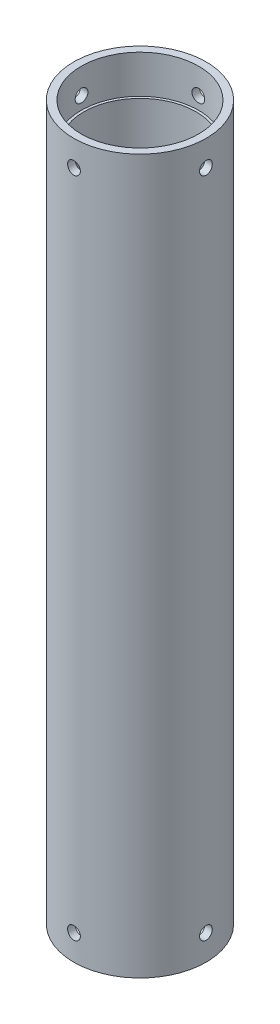
SolidWorks part; units mm, degrees
material "6061-T6 (SS)"
ref_plane "정면" through (0, 0, 0) normal (0, 0, 1) x (1, 0, 0)
ref_plane "윗면" through (0, 0, 0) normal (0, 1, 0) x (1, 0, 0)
ref_plane "우측면" through (0, 0, 0) normal (1, 0, 0) x (0, 0, -1)
sketch "스케치1" plane through (0, 0, 0) normal (0, 1, 0) x (1, 0, 0)
  circle A0 centre (0, 0) radius 26
  circle A1 centre (0, 0) radius 22.05
  dimension "D1" = 52
  dimension "D2" = 44.1
extrude "보스-돌출1" add sketch "스케치1" along normal blind 280
sketch "스케치2" plane through (0, 0, 0) normal (0, -1, 0) x (1, 0, 0)
  circle A0 centre (0, 0) radius 23.05
  dimension "D1" = 46.1
sketch "스케치5" plane through (0, 280, 0) normal (0, 1, 0) x (1, 0, 0)
  circle A0 centre (0, 0) radius 23.05
  dimension "D1" = 46.1
extrude "컷-돌출2" cut sketch "스케치5" against normal blind 15
extrude "컷-돌출3" cut sketch "스케치2" against normal blind 15 contours A0
sketch "스케치6" plane through (0, 0, 0) normal (0, 0, 1) x (1, 0, 0)
  line L0 (0, 0) -> (0, 10)
  line L1 (0, -29.7) -> (0, 29.7) construction
  line L2 (0, 10) -> (0, 320)
  circle A0 centre (0, 10) radius 2.5
  dimension "D2" = 5
  dimension "D1" = 10
extrude "컷-돌출4" cut sketch "스케치6" against normal blind 47 and the other way blind 46 contours A0
sketch "스케치7" plane through (0, 0, 0) normal (0, 0, 1) x (1, 0, 0)
  line L1 (0, 0) -> (0, 10)
  line L3 (0, 10) -> (0, 320)
  line L4 (0, -29.7) -> (0, 29.7) construction
  dimension "D1" = 10
sketch "스케치8" plane through (0, 0, 0) normal (1, 0, 0) x (0, 0, -1)
  line L0 (0, 0) -> (0, 10) construction
  line L1 (0, 29.7) -> (0, -29.7) construction
  circle A0 centre (0, 9.9771) radius 2.5
  dimension "D1" = 5
extrude "컷-돌출5" cut sketch "스케치8" along normal blind 60 and the other way blind 58 contours A0
sketch "스케치9" plane through (0, 0, 0) normal (0, 0, 1) x (1, 0, 0)
  line L0 (0, 10) -> (0, 270)
  circle A0 centre (0, 270) radius 2.5
  dimension "D2" = 5
  dimension "D1" = 260
extrude "컷-돌출6" cut sketch "스케치9" along normal blind 80 and the other way blind 61 contours A0
sketch "스케치10" plane through (0, 0, 0) normal (1, 0, 0) x (0, 0, -1)
  line L0 (0, 10) -> (0, 320) construction
  line L1 (29.7, 0) -> (-29.7, 0) construction
  circle A0 centre (0, 270) radius 2.5
  dimension "D1" = 5
  dimension "D2" = 270
extrude "컷-돌출7" cut sketch "스케치10" along normal blind 102 and the other way blind 81 contours A0
